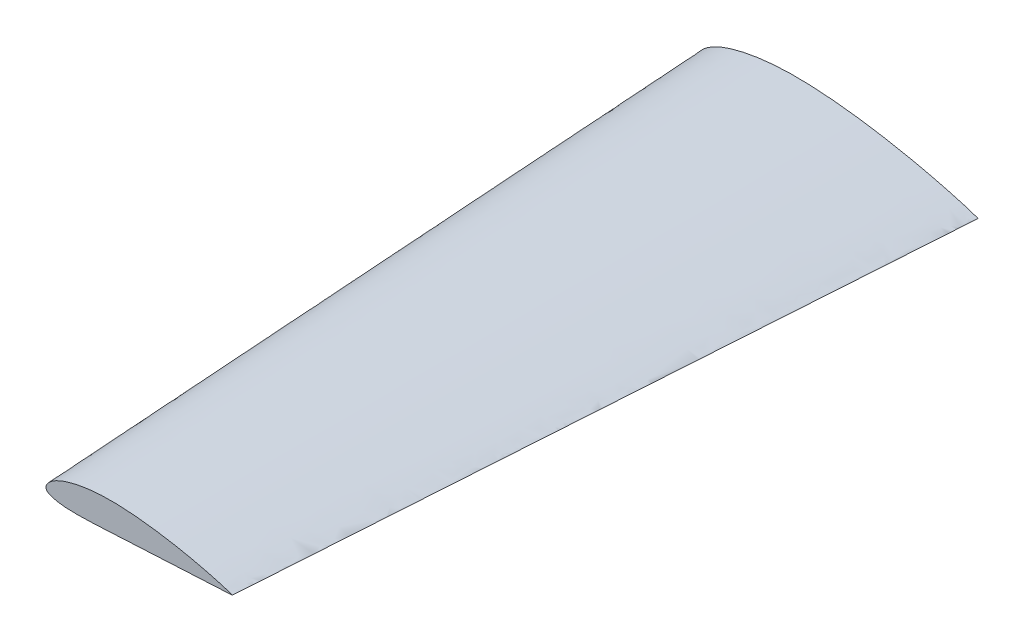
SolidWorks part; units mm, degrees
ref_plane "Front Plane" through (0, 0, 0) normal (0, 0, 1) x (1, 0, 0)
ref_plane "Top Plane" through (0, 0, 0) normal (0, 1, 0) x (1, 0, 0)
ref_plane "Right Plane" through (0, 0, 0) normal (1, 0, 0) x (0, 0, -1)
curve "Curve1"
  spline degree 3 poles (9.7985, -0.0101, 0) (10.0517, -0.0061, 0) (9.7941, 0.0639, 0) (9.6371, 0.13, 0) (9.3002, 0.2252, 0) (8.9472, 0.3239, 0) (8.5157, 0.4347, 0) (8.0277, 0.5506, 0) (7.4869, 0.669, 0) (6.9039, 0.7838, 0) (6.288, 0.8896, 0) (5.6501, 0.9819, 0) (5.0011, 1.0572, 0) (4.3519, 1.1116, 0) (3.7136, 1.1396, 0) (3.0969, 1.1357, 0) (2.5125, 1.0976, 0) (1.9706, 1.0275, 0) (1.4804, 0.9294, 0) (1.0497, 0.8092, 0) (0.6843, 0.6701, 0) (0.3955, 0.5111, 0) (0.1773, 0.3506, 0) (0.0418, 0.1857, 0) (-0.0189, 0.0201, 0) (0.0701, -0.2026, 0) (0.4183, -0.3088, 0) (0.8868, -0.4017, 0) (1.5115, -0.4228, 0) (2.2575, -0.4113, 0) (3.1114, -0.3688, 0) (4.037, -0.3227, 0) (5.0002, -0.2723, 0) (5.9629, -0.216, 0) (6.8892, -0.1599, 0) (7.7407, -0.1144, 0) (8.4945, -0.08, 0) (9.0924, -0.0501, 0) (9.587, -0.0383, 0) (9.7985, -0.0101, 0) (10.0517, -0.0061, 0) (9.7941, 0.0639, 0) knots -0.040926 -0.018505 -0.004679 0 0.004956 0.019501 0.034134 0.052405 0.073994 0.098493 0.125475 0.154452 0.184909 0.216327 0.248169 0.279909 0.31103 0.34105 0.369546 0.396131 0.420447 0.44218 0.461103 0.477136 0.490041 0.500148 0.508078 0.514148 0.532731 0.555553 0.585739 0.622464 0.664407 0.709926 0.757276 0.804639 0.850179 0.892142 0.928906 0.959074 0.981495 0.995321 1 1.004956 1.019501 1.034134 periodic
sketch "Sketch2" plane through (0, 0, 0) normal (0, 0, 1) x (1, 0, 0)
  spline S1 degree 3 poles (117.5826, -0.1218) (120.6206, -0.0738) (117.5295, 0.7666) (115.6455, 1.5595) (111.6027, 2.7021) (107.3662, 3.8862) (102.189, 5.2163) (96.3326, 6.6067) (89.843, 8.0282) (82.8463, 9.4052) (75.4562, 10.6755) (67.8012, 11.7831) (60.0126, 12.6862) (52.2232, 13.3394) (44.5632, 13.6758) (37.1624, 13.6282) (30.1502, 13.1707) (23.6476, 12.3301) (17.7647, 11.1527) (12.5963, 9.7107) (8.2116, 8.0409) (4.7465, 6.1331) (2.1274, 4.2076) (0.5014, 2.2286) (-0.2267, 0.2414) (0.8411, -2.4312) (5.0192, -3.7059) (10.6417, -4.8203) (18.1379, -5.0732) (27.0897, -4.9359) (37.3366, -4.4251) (48.4443, -3.8718) (60.0024, -3.2677) (71.5545, -2.5916) (82.6707, -1.9191) (92.8884, -1.3725) (101.9343, -0.9595) (109.1084, -0.6008) (115.0438, -0.4597) (117.5826, -0.1218) (120.6206, -0.0738) (117.5295, 0.7666) knots -0.040926 -0.018505 -0.004679 0 0.004956 0.019501 0.034134 0.052405 0.073994 0.098493 0.125475 0.154452 0.184909 0.216327 0.248169 0.279909 0.31103 0.34105 0.369546 0.396131 0.420447 0.44218 0.461103 0.477136 0.490041 0.500148 0.508078 0.514148 0.532731 0.555553 0.585739 0.622464 0.664407 0.709926 0.757276 0.804639 0.850179 0.892142 0.928906 0.959074 0.981495 0.995321 1 1.004956 1.019501 1.034134 only from (120, 0) to (120, 0)
ref_plane "Plane1" through (0, 0, 300) normal (0, 0, 1) x (1, 0, 0)
sketch "Sketch3" plane through (0, 0, 300) normal (0, 0, 1) x (1, 0, 0)
  spline S1 degree 3 poles (98.3884, -0.0812) (100.4137, -0.0492) (98.353, 0.511) (97.097, 1.0397) (94.4018, 1.8014) (91.5775, 2.5908) (88.126, 3.4775) (84.2217, 4.4045) (79.8953, 5.3522) (75.2309, 6.2701) (70.3041, 7.117) (65.2008, 7.8554) (60.0084, 8.4575) (54.8154, 8.893) (49.7088, 9.1172) (44.775, 9.0855) (40.1001, 8.7805) (35.765, 8.22) (31.8431, 7.4352) (28.3976, 6.4738) (25.4744, 5.3606) (23.1643, 4.0887) (21.4182, 2.8051) (20.3343, 1.4858) (19.8489, 0.1609) (20.5607, -1.6208) (23.3461, -2.4706) (27.0945, -3.2135) (32.0919, -3.3821) (38.0598, -3.2906) (44.891, -2.9501) (52.2962, -2.5812) (60.0016, -2.1784) (67.703, -1.7277) (75.1138, -1.2794) (81.9256, -0.915) (87.9562, -0.6397) (92.7389, -0.4005) (96.6958, -0.3065) (98.3884, -0.0812) (100.4137, -0.0492) (98.353, 0.511) knots -0.040926 -0.018505 -0.004679 0 0.004956 0.019501 0.034134 0.052405 0.073994 0.098493 0.125475 0.154452 0.184909 0.216327 0.248169 0.279909 0.31103 0.34105 0.369546 0.396131 0.420447 0.44218 0.461103 0.477136 0.490041 0.500148 0.508078 0.514148 0.532731 0.555553 0.585739 0.622464 0.664407 0.709926 0.757276 0.804639 0.850179 0.892142 0.928906 0.959074 0.981495 0.995321 1 1.004956 1.019501 1.034134 only from (100, 0) to (100, 0)
  dimension "D1" = 20
loft "Loft1" add profiles "Sketch2", "Sketch3"
